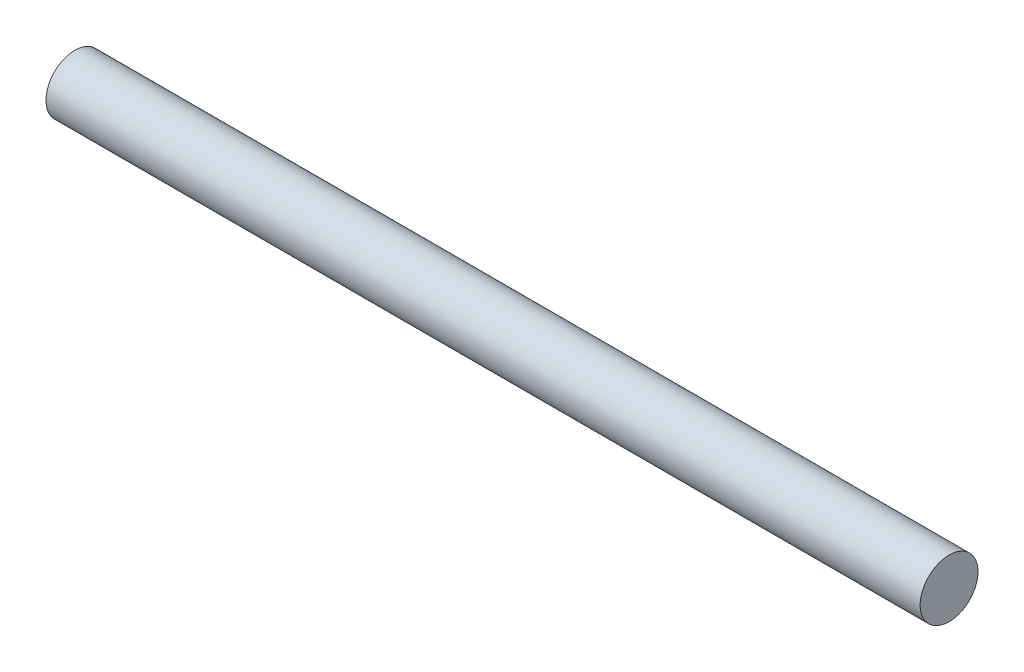
SolidWorks part; units mm, degrees
ref_plane "Front Plane" through (0, 0, 0) normal (0, 0, 1) x (1, 0, 0)
ref_plane "Top Plane" through (0, 0, 0) normal (0, 1, 0) x (1, 0, 0)
ref_plane "Right Plane" through (0, 0, 0) normal (1, 0, 0) x (0, 0, -1)
sketch "Sketch2" plane through (0, 0, 0) normal (1, 0, 0) x (0, 0, -1)
  circle A0 centre (0, 0) radius 1.985
  dimension "D1" = 3.97
extrude "Boss-Extrude1" add sketch "Sketch2" along normal blind 60
